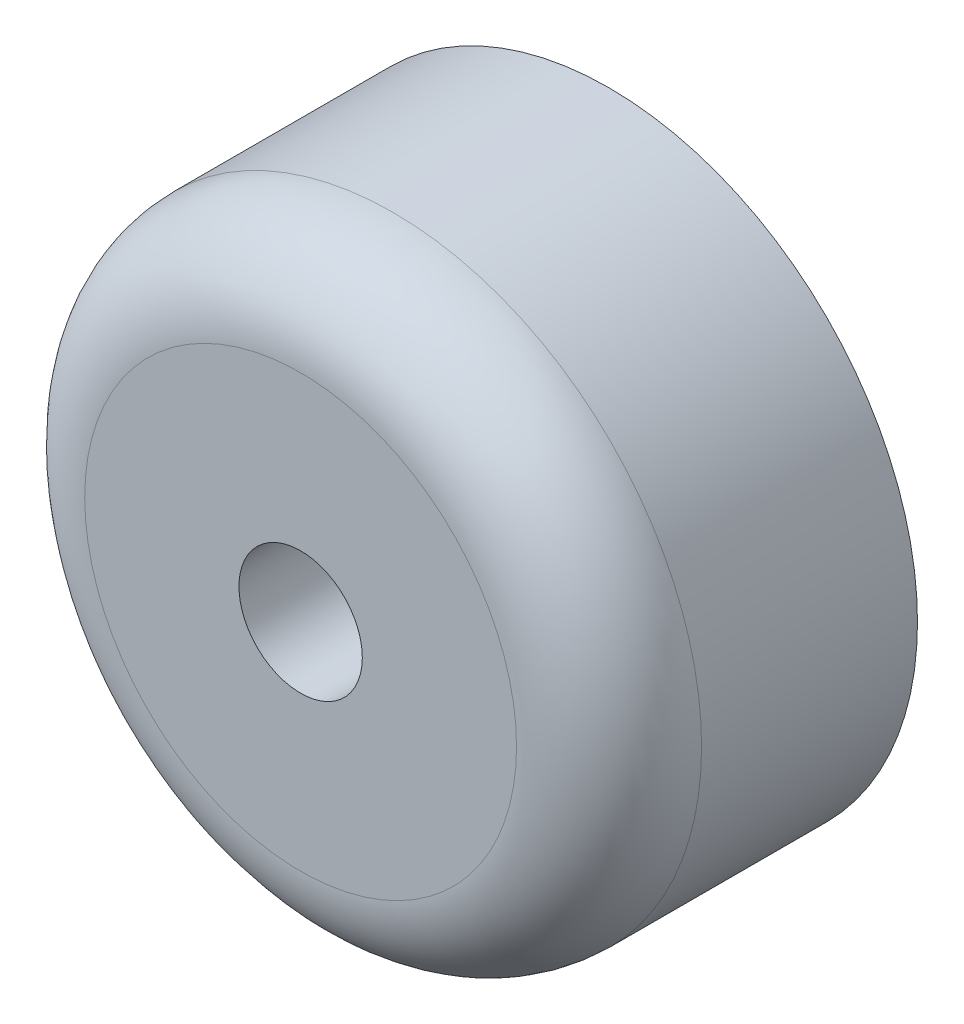
SolidWorks part; units mm, degrees
ref_plane "Front Plane" through (0, 0, 0) normal (0, 0, 1) x (1, 0, 0)
ref_plane "Top Plane" through (0, 0, 0) normal (0, 1, 0) x (1, 0, 0)
ref_plane "Right Plane" through (0, 0, 0) normal (1, 0, 0) x (0, 0, -1)
sketch "Sketch1" plane through (0, 0, 0) normal (0, 0, 1) x (1, 0, 0)
  line L0 (-40, -3.6658) -> (40, -3.6658) construction
  line L1 (-40, -17.9158) -> (-40, 10.5842) construction
  line L2 (40, 10.5842) -> (40, -17.9158) construction
  circle A0 centre (0, -3.6658) radius 10
extrude "Boss-Extrude1" add sketch "Sketch1" along normal blind 10
fillet "Fillet1" radius 3 1 edges at (10, -3.6658, 10)
sketch "Sketch2" plane through (0, 0, 10) normal (0, 0, 1) x (1, 0, 0)
  circle A0 centre (0, -3.6658) radius 2
extrude "Cut-Extrude1" cut sketch "Sketch2" against normal blind 7
